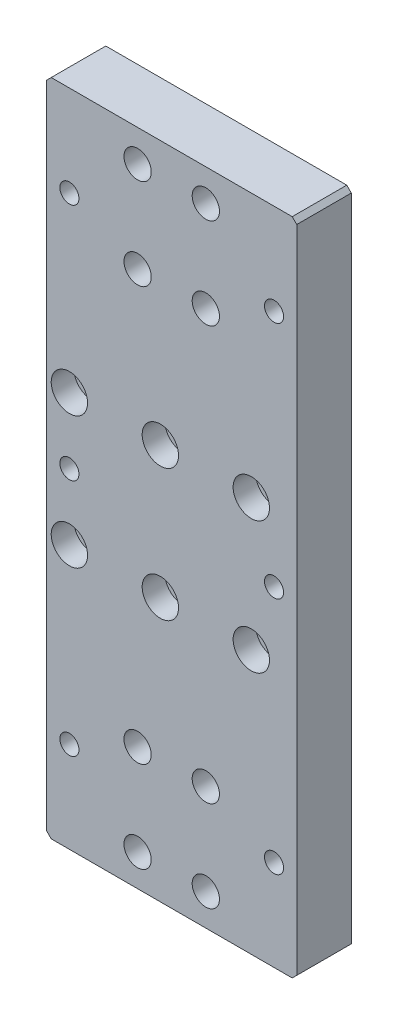
SolidWorks part; units mm, degrees
material "6061 合金"
ref_plane "前视基准面" through (0, 0, 0) normal (0, 0, 1) x (1, 0, 0)
ref_plane "上视基准面" through (0, 0, 0) normal (0, 1, 0) x (1, 0, 0)
ref_plane "右视基准面" through (0, 0, 0) normal (1, 0, 0) x (0, 0, -1)
sketch "草图1" plane through (0, 0, 0) normal (0, 0, 1) x (1, 0, 0)
  line L1 (-52.37, 44.8756) -> (2.63, 44.8756)
  line L2 (-52.37, 44.8756) -> (-52.37, -100.1244)
  line L3 (-52.37, -100.1244) -> (2.63, -100.1244)
  line L4 (2.63, 44.8756) -> (2.63, -100.1244)
  dimension "D1" = 55
  dimension "D2" = 145
extrude "凸台-拉伸1" add sketch "草图1" along normal blind 12
hole_wizard "M3 六角头螺栓的柱形沉头孔1" positions "草图3" profile "草图2" counterbore size "M3" standard "GB" end condition through all
sketch "草图3" plane through (0, 0, 12) normal (0, 0, 1) x (1, 0, 0)
  line L1 (2.63, 44.8756) -> (-52.37, 44.8756) construction
  line L2 (-24.87, 44.8756) -> (-24.87, 19.2073) construction
  point P0 (-32.37, 37.8756)
  point P2 (-17.37, 37.8756)
  point P4 (-17.37, 17.8756)
  point P6 (-32.37, 17.8756)
  dimension "D1" = 20
  dimension "D2" = 15
  dimension "D4" = 7
sketch "草图2" plane through (-32.37, 37.8756, 12) normal (1, 0, 0) x (0, -1, 0)
  line L0 (0, 0) -> (0, 12)
  line L1 (0, 12) -> (1.75, 12)
  line L3 (1.75, 12) -> (1.75, 5)
  line L4 (1.75, 5) -> (3, 5)
  line L5 (3, 5) -> (3, 0)
  line L7 (3, 0) -> (0, 0)
  line L11 (0, -6.35) -> (0, 107.95) construction
  dimension "通孔孔直径" = 3.5
  dimension "通孔孔深度" = 12
  dimension "柱形沉头孔直径" = 6
  dimension "柱形沉头孔深度" = 5
ref_plane "基准面1" through (-24.87, 0, 0) normal (1, 0, 0) x (0, 0, -1)
ref_plane "基准面2" through (0, -27.6244, 0) normal (0, 1, 0) x (1, 0, 0)
mirror "镜向1" about plane through (0, -27.6244, 0) normal (0, 1, 0) of "M3 六角头螺栓的柱形沉头孔1"
sketch "草图4" plane through (2.63, -37.7544, 0) normal (-1, 0, 0) x (0, 1, 0)
  line L1 (-4.37, -1.5) -> (24.63, -1.5)
  line L2 (-4.37, -1.5) -> (-4.37, -12)
  line L3 (-4.37, -12) -> (24.63, -12)
  line L4 (24.63, -1.5) -> (24.63, -12)
  line L5 (10.13, -12) -> (10.13, -7.4319) construction
  line L8 (82.63, -12) -> (-62.37, -12) construction
  dimension "D1" = 29
  dimension "D2" = 10.5
hole_wizard "打孔尺寸(%根据)内六角圆柱头螺钉的类型1" positions "草图6" profile "草图5" counterbore size "M4" standard "GB" end condition through all
sketch "草图6" plane through (27.37, 27.6244, 12) normal (0, 0, 1) x (1, 0, 0)
  line L0 (-79.7399, -55.2487) -> (-64.3015, -55.2487) construction
  line L1 (-79.7399, 17.2513) -> (-79.7399, -127.7487) construction
  point P0 (-74.7399, -40.7487)
  point P3 (-54.7399, -40.7487)
  point P6 (-34.7399, -40.7487)
  point P9 (-34.7399, -69.7487)
  point P12 (-54.7399, -69.7487)
  point P15 (-74.7399, -69.7487)
  dimension "D1" = 29
  dimension "D2" = 5
  dimension "D3" = 20
  dimension "D4" = 20
sketch "草图5" plane through (-47.37, -13.1244, 12) normal (1, 0, 0) x (0, -1, 0)
  line L0 (0, 0) -> (0, 12)
  line L1 (0, 12) -> (2.25, 12)
  line L3 (2.25, 12) -> (2.25, 5)
  line L4 (2.25, 5) -> (4, 5)
  line L5 (4, 5) -> (4, 0)
  line L7 (4, 0) -> (0, 0)
  line L11 (0, -6.35) -> (0, 107.95) construction
  dimension "通孔孔直径" = 4.5
  dimension "通孔孔深度" = 12
  dimension "柱形沉头孔直径" = 8
  dimension "柱形沉头孔深度" = 5
hole_wizard "M5 螺纹孔1" positions "草图8" profile "草图7" tap size "M5" standard "GB"
sketch "草图8" plane through (0, 0, 12) normal (0, 0, 1) x (1, 0, 0)
  line L0 (6.6, -27.6244) -> (-6.6, -27.6244) construction
  line L1 (-24.87, 44.8756) -> (-24.87, 61.0048) construction
  line L2 (2.63, 44.8756) -> (-52.37, 44.8756) construction
  line L3 (-24.87, -6.6) -> (-24.87, 6.6) construction
  line L5 (-52.37, -27.6244) -> (-72.5707, -27.6244) construction
  line L6 (-52.37, 44.8756) -> (-52.37, -100.1244) construction
  point P0 (-47.37, 24.8756)
  point P2 (-2.37, 24.8756)
  point P4 (-2.37, -27.6244)
  point P8 (-47.37, -27.6244)
  point P10 (-47.37, -80.1244)
  point P12 (-2.37, -80.1244)
  dimension "D1" = 45
  dimension "D2" = 105
sketch "草图7" plane through (-47.37, 24.8756, 12) normal (1, 0, 0) x (0, -1, 0)
  line L0 (0, 0) -> (0, 15.2618)
  line L1 (0, 15.2618) -> (2.1, 14)
  line L2 (2.1, 14) -> (2.1, 0)
  line L5 (2.1, 0) -> (0, 0)
  line L10 (0, 15.2618) -> (-2.1, 14) construction
  line L11 (0, -6.35) -> (0, 107.95) construction
  dimension "螺纹孔钻头直径" = 4.2
  dimension "螺纹孔钻头深度" = 14
  dimension "导头角度" = 118
cosmetic thread "孔螺蚊线1" parameters "D1"=10, "D2"=5
cosmetic thread "孔螺蚊线2" parameters "D1"=10, "D2"=5
cosmetic thread "孔螺蚊线3" parameters "D1"=10, "D2"=5
cosmetic thread "孔螺蚊线4" parameters "D1"=10, "D2"=5
cosmetic thread "孔螺蚊线5" parameters "D1"=10, "D2"=5
cosmetic thread "孔螺蚊线6" parameters "D1"=10, "D2"=5
hole_wizard "M3 螺纹孔1" positions "草图10" profile "草图9" tap size "M3" standard "GB"
sketch "草图10" plane through (0, 0, 0) normal (0, 0, -1) x (-1, 0, 0)
  line L0 (24.87, -100.1244) -> (24.87, -75.4854) construction
  line L1 (52.37, -100.1244) -> (-2.63, -100.1244) construction
  point P0 (29.37, -61.1244)
  point P2 (20.37, -61.1244)
  dimension "D1" = 9
  dimension "D2" = 39
sketch "草图9" plane through (-29.37, -61.1244, 0) normal (1, 0, 0) x (0, 1, 0)
  line L0 (0, 0) -> (0, 9.2511)
  line L1 (0, 9.2511) -> (1.25, 8.5)
  line L2 (1.25, 8.5) -> (1.25, 0)
  line L5 (1.25, 0) -> (0, 0)
  line L10 (0, 9.2511) -> (-1.25, 8.5) construction
  line L11 (0, -6.35) -> (0, 107.95) construction
  dimension "螺纹孔钻头直径" = 2.5
  dimension "螺纹孔钻头深度" = 8.5
  dimension "导头角度" = 118
cosmetic thread "孔螺蚊线7" parameters "D1"=6, "D2"=3
cosmetic thread "孔螺蚊线8" parameters "D1"=6, "D2"=3
chamfer "倒角1" distance 1 angle 45 4 edges at (-52.37, -100.1244, 6) (2.63, -100.1244, 6) (2.63, 44.8756, 6) (-52.37, 44.8756, 6)
